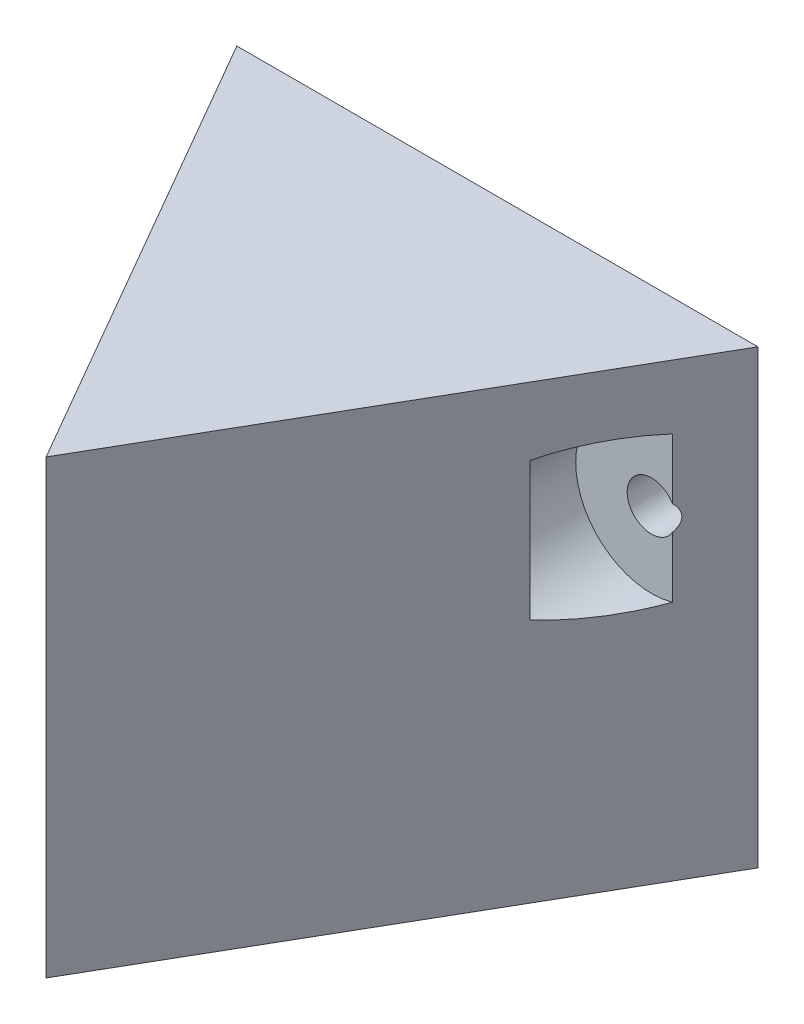
SolidWorks part; units mm, degrees
ref_plane "Alzado" through (0, 0, 0) normal (0, 0, 1) x (1, 0, 0)
ref_plane "Planta" through (0, 0, 0) normal (0, 1, 0) x (1, 0, 0)
ref_plane "Vista lateral" through (0, 0, 0) normal (1, 0, 0) x (0, 0, -1)
sketch "Croquis1" plane through (0, 0, 0) normal (0, 1, 0) x (1, 0, 0)
  line L15 (-28.8675, 0) -> (28.8675, 0)
  line L23 (-28.8675, 0) -> (0, -50)
  line L27 (28.8675, 0) -> (0, -50)
  point P3 (0, 0)
  point P4 (0, 0)
  point P5 (-94.9281, 0)
  point P6 (6.1919, 0)
  point P7 (74.7626, 0)
  point P8 (-37.2242, 0)
  point P9 (-94.9151, 0)
  point P10 (-34.0542, 0)
  point P11 (-26.7208, 0)
  point P12 (18.5851, -4.949)
  point P13 (-24.6217, 0)
  point P14 (-24.6217, 0)
  point P15 (-120.1228, 30.8207)
  point P16 (-24.6217, 0)
  point P17 (0, -43.3013)
  point P18 (-113.1949, 7.2363)
  point P19 (-109.6572, 41.1388)
  point P20 (25.3632, 0)
  point P21 (25.5106, -1.313)
  point P22 (21.5333, -15.5357)
  point P23 (6.3903, -10.0413)
  point P24 (-12.7729, -44.6155)
  point P25 (0, 0)
  point P27 (0, -58.6568)
  dimension "D1" = 60
  dimension "D2" = 50
  dimension "D4" = 60
extrude "Saliente-Extruir1" add sketch "Croquis1" along normal mid plane 50 contours L23 L15 L27
sketch "Croquis6" plane through (0, 0, 0) normal (0, 0, 1) x (1, 0, 0)
  line L0 (-28.8675, 0) -> (0, 0) construction
  line L2 (-28.8675, 0) -> (28.8675, 0) construction
  circle A0 centre (-23.0707, 0) radius 2.7
  circle A2 centre (23.083, 9.8355) radius 2.7
  dimension "D1" = 5.4
  dimension "D2" = 5.4
  dimension "D4" = 47.19
extrude "Cortar-Extruir1" cut sketch "Croquis6" against normal mid plane 30
ref_plane "Plano2" through (0, 0, 6) normal (0, 0, -1) x (-1, 0, 0)
sketch "Croquis7" plane through (0, 0, 6) normal (0, 0, -1) x (-1, 0, 0)
  circle A0 centre (-23.083, 9.8355) radius 8.4
  circle A1 centre (23.0707, 0) radius 8.4
  dimension "D1" = 16.8
  dimension "D2" = 16.8
extrude "Cortar-Extruir2" cut sketch "Croquis7" against normal blind 10
